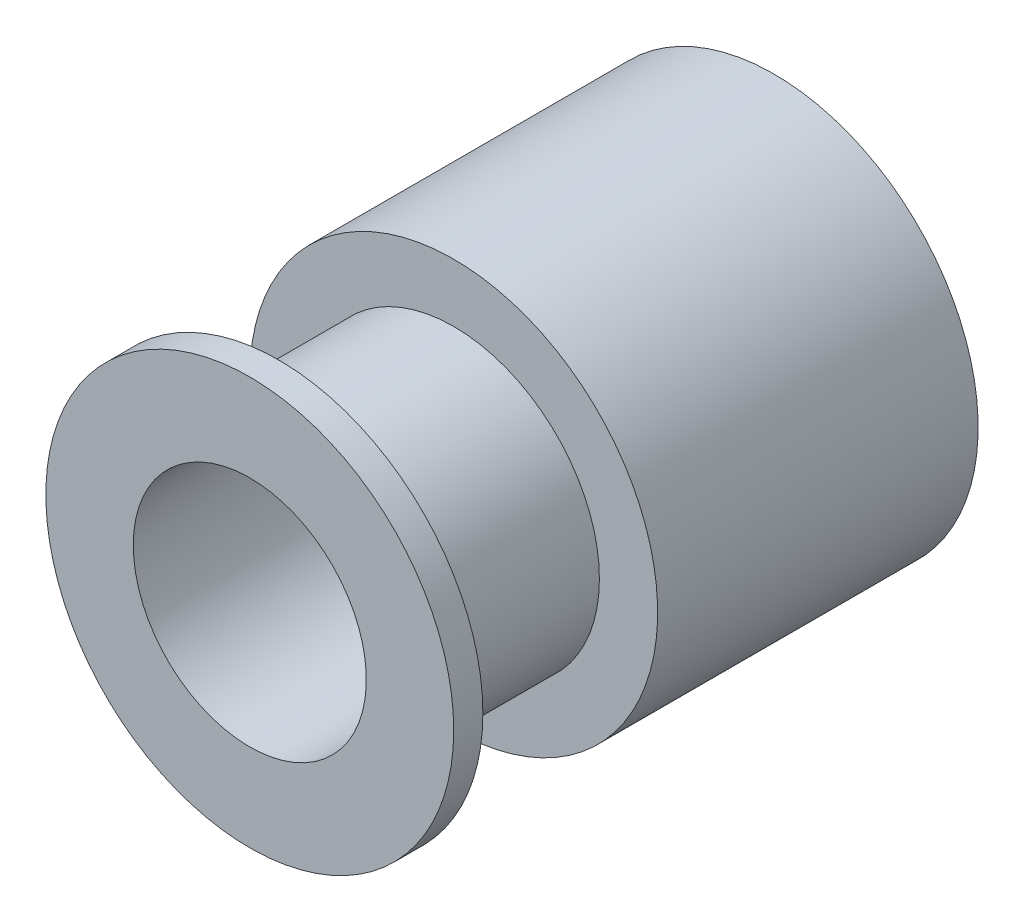
SolidWorks part; units mm, degrees
ref_plane "Спереди" through (0, 0, 0) normal (0, 0, 1) x (1, 0, 0)
ref_plane "Сверху" through (0, 0, 0) normal (0, 1, 0) x (1, 0, 0)
ref_plane "Справа" through (0, 0, 0) normal (1, 0, 0) x (0, 0, -1)
sketch "Эскиз1" plane through (0, 0, 0) normal (0, 0, 1) x (1, 0, 0)
  circle A0 centre (0, 0) radius 7
  dimension "D1" = 14
extrude "Бобышка-Вытянуть1" add sketch "Эскиз1" along normal blind 1
sketch "Эскиз2" plane through (0, 0, 0) normal (0, 0, -1) x (-1, 0, 0)
  circle A0 centre (0, 0) radius 5
  dimension "D1" = 10
extrude "Бобышка-Вытянуть2" add sketch "Эскиз2" along normal blind 6
sketch "Эскиз3" plane through (0, 0, -6) normal (0, 0, -1) x (-1, 0, 0)
  circle A0 centre (0, 0) radius 7
  dimension "D1" = 14
extrude "Бобышка-Вытянуть3" add sketch "Эскиз3" along normal blind 11
sketch "Эскиз4" plane through (0, 0, -17) normal (0, 0, -1) x (-1, 0, 0)
  circle A0 centre (0, 0) radius 4
  dimension "D1" = 8
extrude "Вырез-Вытянуть1" cut sketch "Эскиз4" against normal through all
